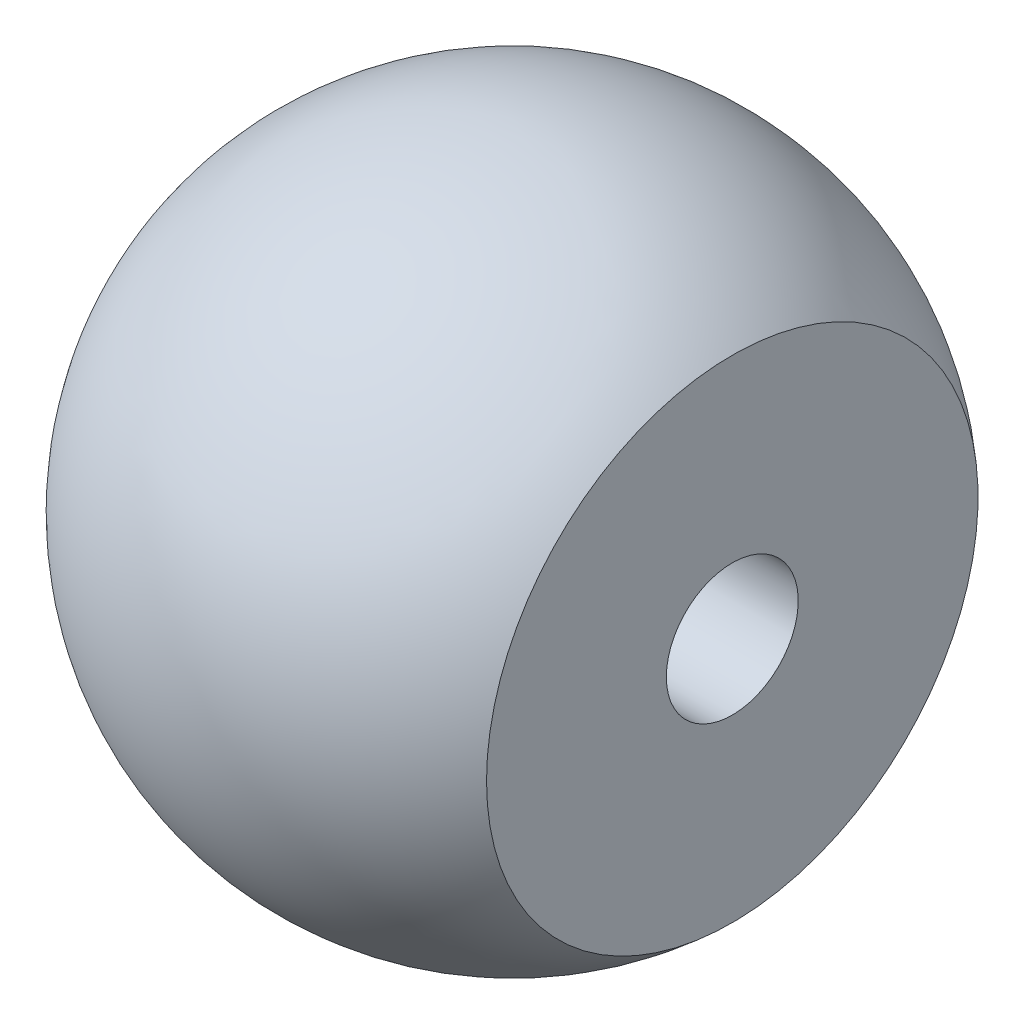
SolidWorks part; units mm, degrees
ref_plane "Front Plane" through (0, 0, 0) normal (0, 0, 1) x (1, 0, 0)
ref_plane "Top Plane" through (0, 0, 0) normal (0, 1, 0) x (1, 0, 0)
ref_plane "Right Plane" through (0, 0, 0) normal (1, 0, 0) x (0, 0, -1)
sketch "Sketch1" plane through (0, 0, 0) normal (0, 0, 1) x (1, 0, 0)
  line L0 (0, 30) -> (0, -30)
  arc A0 (0, -30) -> (0, 30) centre (0, 0) ccw
  point P4 (0, 8.8452)
  dimension "D1" = 30
revolve "Revolve1" add sketch "Sketch1" angle 360 about L0
sketch "Sketch2" plane through (0, 0, 0) normal (0, 0, 1) x (1, 0, 0)
  line L0 (20, 22.3607) -> (20, -22.3607)
  circle A0 centre (0, 0) radius 30 construction
  circle A1 centre (0, 0) radius 30
  point P2 (20, 22.3607)
  point P6 (20, -22.3607)
  dimension "D1" = 20
extrude "Cut-Extrude-Thin1" cut sketch "Sketch2" against normal through all both and the other way through all thin contours L0
sketch "Sketch3" plane through (20, 0, 0) normal (1, 0, 0) x (0, 0, -1)
  circle A0 centre (0, 0) radius 6
  circle A1 centre (0, 0) radius 22.3607
  circle A2 centre (0, 0) radius 22.3607
  dimension "D2" = 12
  dimension "D1" = 0
extrude "Cut-Extrude1" cut sketch "Sketch3" against normal blind 12 and the other way through all contours A0
